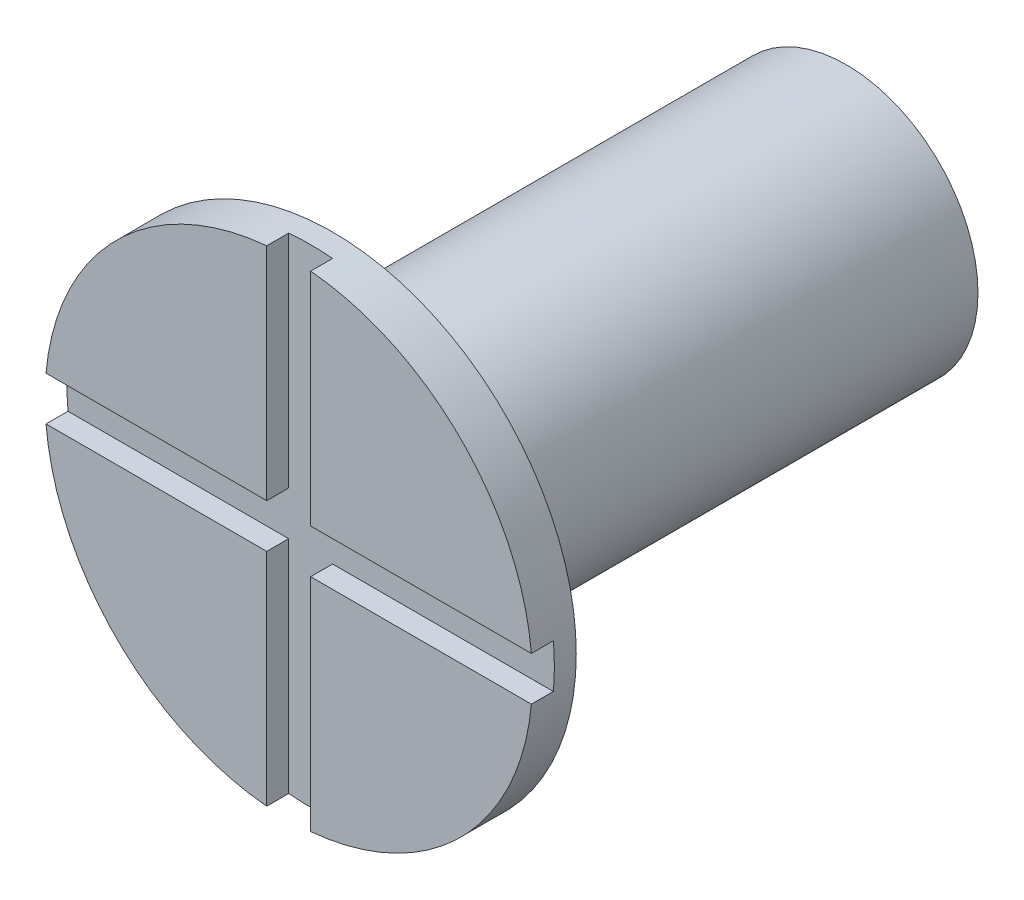
SolidWorks part; units mm, degrees
material "1060 Alloy"
ref_plane "Front Plane" through (0, 0, 0) normal (0, 0, 1) x (1, 0, 0)
ref_plane "Top Plane" through (0, 0, 0) normal (0, 1, 0) x (1, 0, 0)
ref_plane "Right Plane" through (0, 0, 0) normal (1, 0, 0) x (0, 0, -1)
sketch "Sketch1" plane through (0, 0, 0) normal (0, 0, 1) x (1, 0, 0)
  circle A0 centre (0, 0) radius 1.5
  dimension "D1" = 3
extrude "Boss-Extrude1" add sketch "Sketch1" along normal blind 6.35
sketch "Sketch3" plane through (0, 0, 6.35) normal (0, 0, 1) x (1, 0, 0)
  circle A0 centre (0, 0) radius 2.775
  dimension "D1" = 5.55
extrude "Boss-Extrude3" add sketch "Sketch3" against normal blind 0.5
sketch "Sketch4" plane through (0, 0, 6.35) normal (0, 0, 1) x (1, 0, 0)
  line L0 (0, 3.0043) -> (0, -3.0043)
  line L1 (-3.0043, 0) -> (3.0043, 0)
  circle A0 centre (0, 0) radius 3.0043 construction
extrude "Cut-Extrude-Thin1" cut sketch "Sketch4" against normal blind 0.25 thin thin type mid plane wall 0.5
